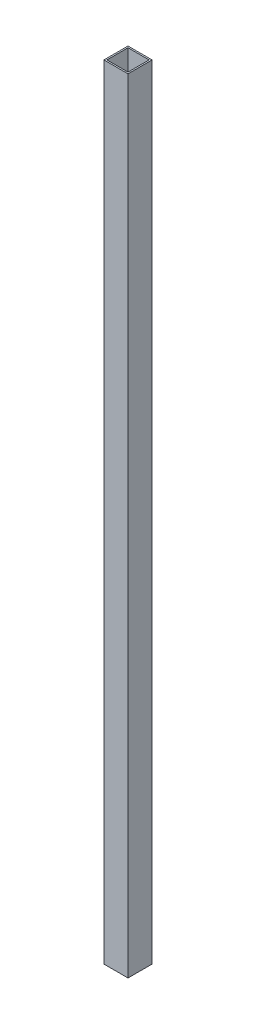
SolidWorks part; units mm, degrees
ref_plane "Front Plane" through (0, 0, 0) normal (0, 0, 1) x (1, 0, 0)
ref_plane "Top Plane" through (0, 0, 0) normal (0, 1, 0) x (1, 0, 0)
ref_plane "Right Plane" through (0, 0, 0) normal (1, 0, 0) x (0, 0, -1)
sketch "Sketch1" plane through (0, 0, 0) normal (0, 1, 0) x (1, 0, 0)
  line L1 (12.7, 12.7) -> (-12.7, 12.7)
  line L2 (12.7, 12.7) -> (12.7, -12.7)
  line L3 (12.7, -12.7) -> (-12.7, -12.7)
  line L4 (-12.7, 12.7) -> (-12.7, -12.7)
  line L5 (12.7, 12.7) -> (-12.7, -12.7) construction
  line L6 (12.7, -12.7) -> (-12.7, 12.7) construction
  line L7 (11.1125, 11.1125) -> (-11.1125, 11.1125)
  line L8 (11.1125, 11.1125) -> (11.1125, -11.1125)
  line L9 (11.1125, -11.1125) -> (-11.1125, -11.1125)
  line L10 (-11.1125, 11.1125) -> (-11.1125, -11.1125)
  line L11 (11.1125, 11.1125) -> (-11.1125, -11.1125) construction
  line L12 (11.1125, -11.1125) -> (-11.1125, 11.1125) construction
  point P0 (0, 0)
  point P6 (0, 0)
  dimension "D1" = 25.4
  dimension "D2" = 25.4
  dimension "D3" = 1.5875
  dimension "D4" = 1.5875
extrude "Boss-Extrude1" add sketch "Sketch1" along normal blind 825.5
